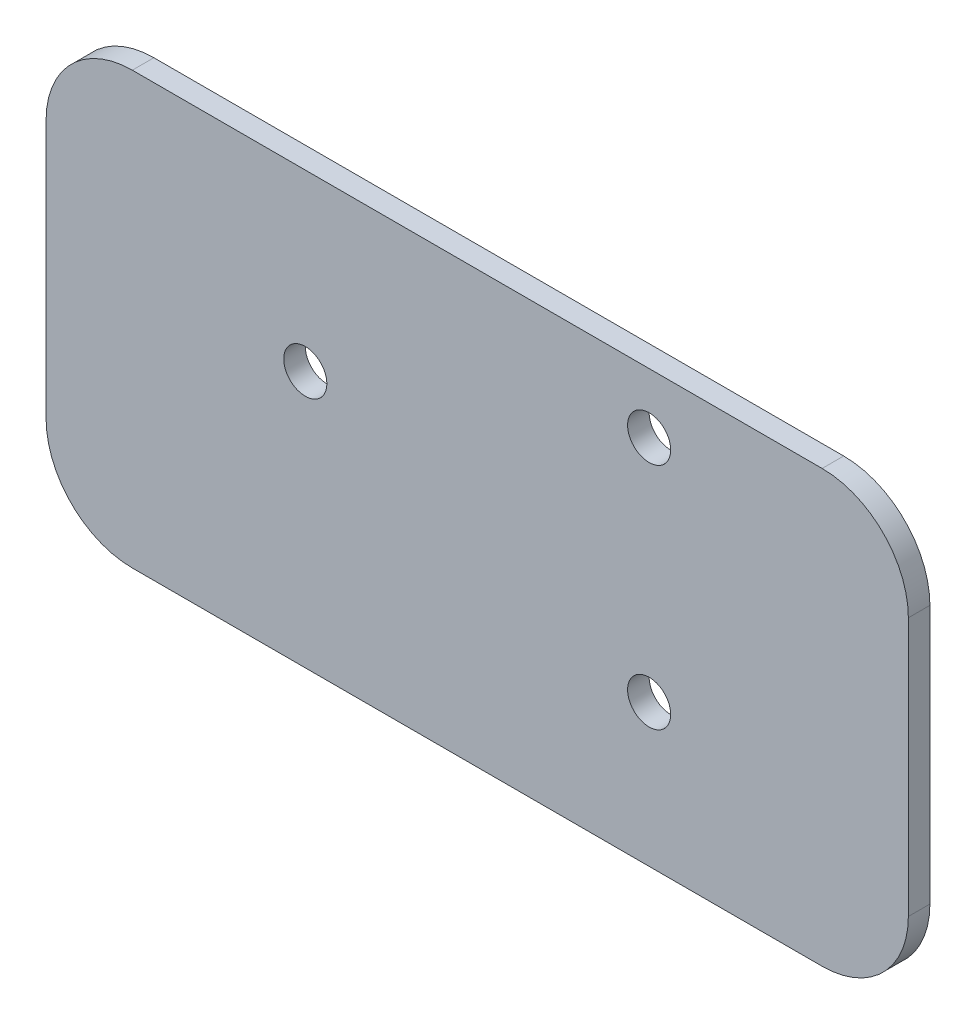
SolidWorks part; units mm, degrees
ref_plane "Front Plane" through (0, 0, 0) normal (0, 0, 1) x (1, 0, 0)
ref_plane "Top Plane" through (0, 0, 0) normal (0, 1, 0) x (1, 0, 0)
ref_plane "Right Plane" through (0, 0, 0) normal (1, 0, 0) x (0, 0, -1)
sketch "Sketch1" plane through (0, 0, 0) normal (0, 0, 1) x (1, 0, 0)
  line L0 (175.3841, 140.3257) -> (588.1705, 140.3257) construction
  line L1 (175.3841, 140.3257) -> (588.1705, 140.3257) construction
  line L2 (607.2205, 150.4857) -> (777.9141, 150.4857) construction
  line L3 (607.2205, 150.4857) -> (777.9141, 150.4857)
  line L4 (409.7794, 139.0557) -> (511.3794, 139.0557)
  line L5 (400.9171, 140.3257) -> (527.9171, 140.3257) construction
  line L6 (397.0794, 126.3557) -> (397.0794, 88.2557)
  line L7 (409.7794, 75.5557) -> (511.3794, 75.5557)
  line L8 (524.0794, 126.3557) -> (524.0794, 88.2557)
  line L9 (460.5794, 139.0557) -> (460.5794, 75.5557) construction
  line L10 (435.2555, 113.3793) -> (435.2555, 130.248) construction
  line L11 (435.2555, 130.248) -> (485.9032, 130.248) construction
  circle A0 centre (485.9032, 130.248) radius 3.175 construction
  circle A1 centre (485.9032, 130.248) radius 3.175
  circle A2 centre (485.9032, 96.5107) radius 3.175 construction
  circle A3 centre (435.2555, 113.3793) radius 3.175 construction
  circle A4 centre (485.9032, 96.5107) radius 3.175
  circle A5 centre (435.2555, 113.3793) radius 3.175
  arc A6 (511.3794, 139.0557) -> (524.0794, 126.3557) centre (511.3794, 126.3557) cw
  arc A7 (511.3794, 75.5557) -> (524.0794, 88.2557) centre (511.3794, 88.2557) ccw
  arc A8 (397.0794, 88.2557) -> (409.7794, 75.5557) centre (409.7794, 88.2557) ccw
  arc A9 (409.7794, 139.0557) -> (397.0794, 126.3557) centre (409.7794, 126.3557) ccw
  point P29 (460.5794, 130.248)
  dimension "D1" = 12.7
  dimension "D2" = 127
  dimension "D3" = 1.27
  dimension "D4" = 63.5
extrude "Boss-Extrude1" add sketch "Sketch1" along normal blind 3.175 contours L4 A9 L6 A8 L7 A7 L8 A6 A1 A4 A5
